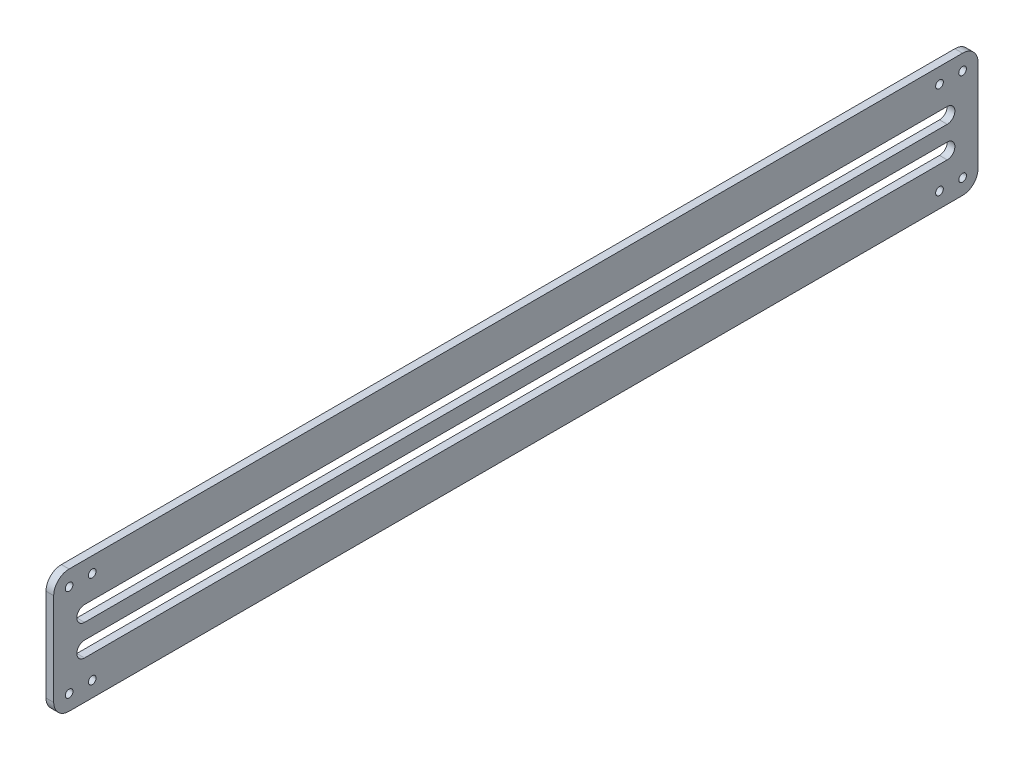
SolidWorks part; units mm, degrees
ref_plane "Front Plane" through (0, 0, 0) normal (0, 0, 1) x (1, 0, 0)
ref_plane "Top Plane" through (0, 0, 0) normal (0, 1, 0) x (1, 0, 0)
ref_plane "Right Plane" through (0, 0, 0) normal (1, 0, 0) x (0, 0, -1)
sketch "Sketch1" plane through (0, 0, 0) normal (1, 0, 0) x (0, 0, -1)
  line L1 (-184.15, -25.4) -> (184.15, -25.4)
  line L2 (-190.5, -19.05) -> (-190.5, 19.05)
  line L3 (-184.15, 25.4) -> (184.15, 25.4)
  line L4 (190.5, -19.05) -> (190.5, 19.05)
  line L5 (-190.5, -25.4) -> (190.5, 25.4) construction
  line L6 (-190.5, 25.4) -> (190.5, -25.4) construction
  arc A0 (184.15, 25.4) -> (190.5, 19.05) centre (184.15, 19.05) cw
  arc A1 (190.5, -19.05) -> (184.15, -25.4) centre (184.15, -19.05) cw
  arc A2 (-184.15, -25.4) -> (-190.5, -19.05) centre (-184.15, -19.05) cw
  arc A3 (-190.5, 19.05) -> (-184.15, 25.4) centre (-184.15, 19.05) cw
  point P0 (0, 0)
  dimension "D3" = 6.35
  dimension "D1" = 381
  dimension "D2" = 50.8
extrude "Outer Cut" add sketch "Sketch1" along normal mid plane 3.175
sketch "Sketch2" plane through (1.5875, 0, 0) normal (1, 0, 0) x (0, 0, -1)
  line L0 (-190.5, 0) -> (190.5, 0) construction
  line L1 (-190.5, 19.05) -> (-190.5, -19.05) construction
  line L2 (190.5, -19.05) -> (190.5, 19.05) construction
  line L3 (-177.8, 6.35) -> (177.8, 6.35) construction
  line L4 (-177.8, 9.525) -> (177.8, 9.525)
  line L5 (-177.8, 3.175) -> (177.8, 3.175)
  line L6 (-177.8, -6.35) -> (177.8, -6.35) construction
  line L7 (-177.8, -9.525) -> (177.8, -9.525)
  line L8 (-177.8, -3.175) -> (177.8, -3.175)
  arc A0 (-177.8, 9.525) -> (-177.8, 3.175) centre (-177.8, 6.35) ccw
  arc A1 (177.8, 3.175) -> (177.8, 9.525) centre (177.8, 6.35) ccw
  arc A2 (-177.8, -9.525) -> (-177.8, -3.175) centre (-177.8, -6.35) cw
  arc A3 (177.8, -3.175) -> (177.8, -9.525) centre (177.8, -6.35) cw
  point P2 (0, 6.35)
  point P16 (0, -6.35)
  dimension "D1" = 6.35
  dimension "D2" = 12.7
  dimension "D3" = 12.7
  dimension "D4" = 12.7
extrude "Slots" cut sketch "Sketch2" against normal through all
sketch "Sketch3" plane through (1.5875, 0, 0) normal (1, 0, 0) x (0, 0, -1)
  line L0 (-190.5, 19.05) -> (-190.5, -19.05) construction
  line L1 (184.15, 25.4) -> (-184.15, 25.4) construction
  line L2 (0, 0) -> (0, 25.4) construction
  line L3 (0, 0) -> (-190.5, 0) construction
  circle A0 centre (-184.15, 19.05) radius 1.5875
  circle A1 centre (-174.625, 19.05) radius 1.5875
  circle A2 centre (-174.625, -19.05) radius 1.5875
  circle A3 centre (-184.15, -19.05) radius 1.5875
  circle A4 centre (174.625, 19.05) radius 1.5875
  circle A5 centre (184.15, 19.05) radius 1.5875
  circle A6 centre (184.15, -19.05) radius 1.5875
  circle A7 centre (174.625, -19.05) radius 1.5875
  dimension "D1" = 3.175
  dimension "D2" = 6.35
  dimension "D3" = 6.35
  dimension "D5" = 9.525
  dimension "D4" = 2
extrude "Mount Holes" cut sketch "Sketch3" against normal through all
